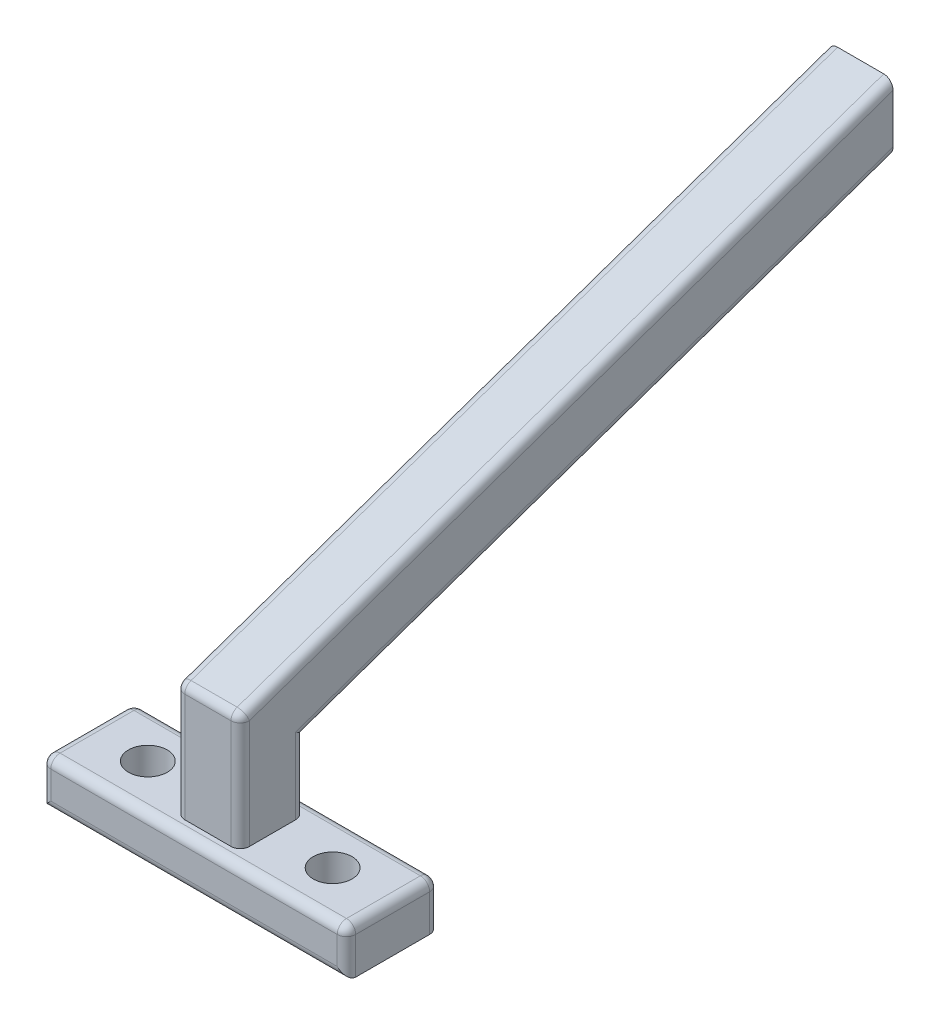
SolidWorks part; units mm, degrees
ref_plane "Front Plane" through (0, 0, 0) normal (1, 0, 0) x (0, 1, 0)
ref_plane "Top Plane" through (0, 0, 0) normal (0, 0, 1) x (0, 1, 0)
ref_plane "Right Plane" through (0, 0, 0) normal (0, 1, 0) x (-1, 0, 0)
sketch "Sketch1" plane through (0, 0, 0) normal (1, 0, 0) x (0, 1, 0)
  line L0 (0, 5) -> (10, 5) construction
  line L1 (0, 0) -> (-5, 0)
  line L2 (0, 0) -> (0, 1.5)
  line L3 (0, 10) -> (-5, 10)
  line L4 (-5, 0) -> (-5, 10)
  line L5 (10, 5) -> (33.3825, -62.15) construction
  line L6 (0, 1.5) -> (7.5126, 1.5)
  line L7 (7.5126, 1.5) -> (29.6764, -62.15)
  line L8 (0, 8.5) -> (12.4874, 8.5)
  line L9 (12.4874, 8.5) -> (36.6878, -60.999)
  line L10 (36.6878, -60.999) -> (37.0886, -62.15)
  line L11 (29.6764, -62.15) -> (37.0886, -62.15)
  line L12 (7.5126, 1.5) -> (30.0772, -63.301) construction
  line L13 (0, 8.5) -> (0, 10)
  dimension "D1" = 5
  dimension "D2" = 10
  dimension "D3" = 67.15
  dimension "D6" = 10
  dimension "D4" = 3.5
  dimension "D5" = 3.5
extrude "Boss-Extrude1" add sketch "Sketch1" along normal blind 7 contours L3 L4 L1 L2 L6 L7 L11 L10 L9 L8 L13
sketch "Sketch2" plane through (7, 0, 0) normal (1, 0, 0) x (0, 1, 0)
  line L1 (-5, 0) -> (0, 0)
  line L2 (-5, 0) -> (-5, 10)
  line L3 (-5, 10) -> (0, 10)
  line L4 (0, 0) -> (0, 10)
extrude "Boss-Extrude2" add sketch "Sketch2" along normal blind 13 and the other way blind 20
sketch "Sketch4" plane through (0, -5, 0) normal (0, -1, 0) x (1, 0, 0)
  line L0 (-13, 5) -> (20, 5) construction
  line L1 (-13, 10) -> (-13, 0) construction
  line L2 (20, 10) -> (20, 0) construction
  line L3 (3.5, 10) -> (3.5, 0) construction
  line L4 (20, 10) -> (-13, 10) construction
  line L5 (20, 0) -> (-13, 0) construction
  circle A0 centre (-6.5, 5) radius 2.1
  circle A1 centre (13.5, 5) radius 2.1
  dimension "D3" = 4.2
  dimension "D1" = 20
  dimension "D2" = 10
extrude "Cut-Extrude1" cut sketch "Sketch4" against normal through all
fillet "Fillet1" radius 1 18 edges at (20, -2.5, 10) (3.5, -5, 10) (-13, -2.5, 10) (3.5, 0, 10) (7, 3.7563, 1.5) (7, 18.5945, -30.325) (7, 24.788, -26.825) (0, 24.788, -26.825) (0, 18.5945, -30.325) (0, 3.7563, 1.5) (7, 6.2437, 8.5) (3.5, 12.4874, 8.5) (0, 6.2437, 8.5) (-13, 0, 5) (-13, -2.5, 0) (20, -2.5, 0) (3.5, 0, 0) (20, 0, 5)
